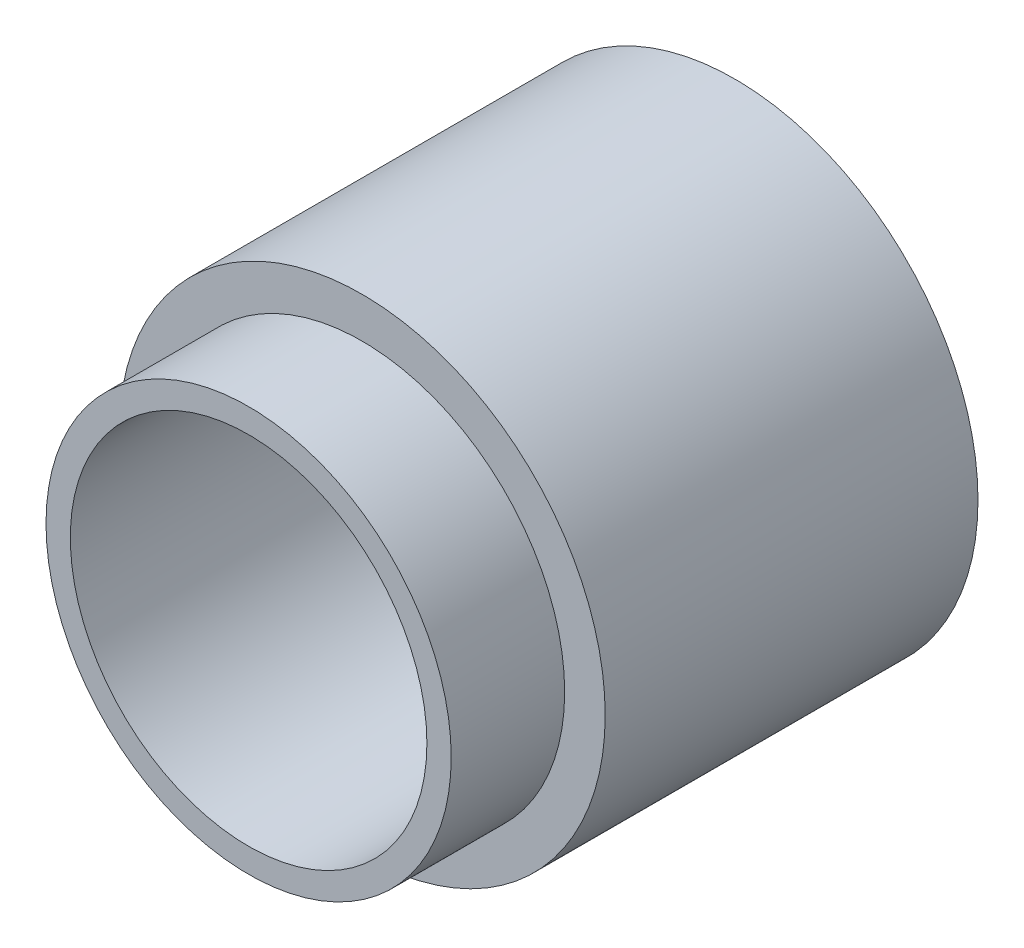
SolidWorks part; units mm, degrees
material "PVAL"
ref_plane "Front" through (0, 0, 0) normal (0, 0, 1) x (1, 0, 0)
ref_plane "Top" through (0, 0, 0) normal (0, 1, 0) x (1, 0, 0)
ref_plane "Right" through (0, 0, 0) normal (1, 0, 0) x (0, 0, -1)
sketch "Sketch1" plane through (0, 0, 0) normal (0, 0, 1) x (1, 0, 0)
  circle A0 centre (0, 0) radius 11
  circle A1 centre (0, 0) radius 12.5
  dimension "D1" = 22
  dimension "D2" = 25
extrude "Boss-Extrude1" add sketch "Sketch1" along normal blind 30
sketch "Sketch2" plane through (0, 0, 30) normal (0, 0, 1) x (1, 0, 0)
  circle A0 centre (0, 0) radius 15
  circle A1 centre (0, 0) radius 12.5 construction
  circle A2 centre (0, 0) radius 12.5
  dimension "D1" = 30
extrude "Boss-Extrude2" add sketch "Sketch2" against normal up to surface (23 mm away) from offset 7 up to face at (12.5, 0, 0)
